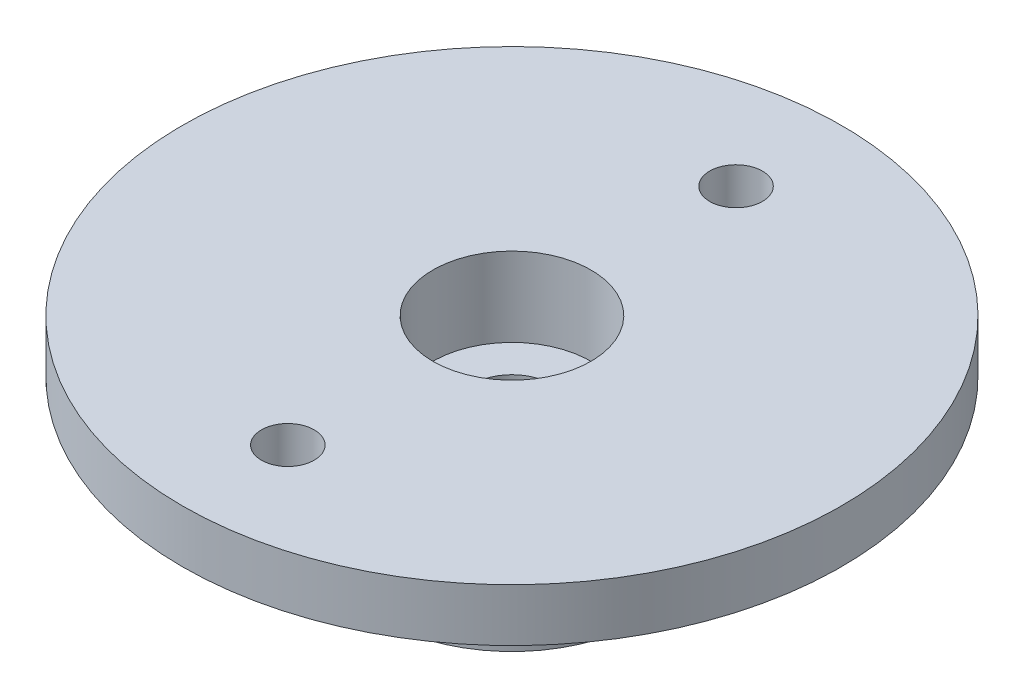
SolidWorks part; units mm, degrees
ref_plane "Front Plane" through (0, 0, 0) normal (0, 0, 1) x (1, 0, 0)
ref_plane "Top Plane" through (0, 0, 0) normal (0, 1, 0) x (1, 0, 0)
ref_plane "Right Plane" through (0, 0, 0) normal (1, 0, 0) x (0, 0, -1)
sketch "Sketch1" plane through (0, 0, 0) normal (0, 1, 0) x (1, 0, 0)
  circle A0 centre (0, 0) radius 12.5
  dimension "D1" = 25
extrude "Boss-Extrude1" add sketch "Sketch1" along normal blind 2
sketch "Sketch2" plane through (0, 0, 0) normal (0, -1, 0) x (1, 0, 0)
  circle A0 centre (0, 0) radius 5
  dimension "D1" = 10
extrude "Boss-Extrude2" add sketch "Sketch2" along normal blind 5.5
sketch "Sketch3" plane through (0, -5.5, 0) normal (0, -1, 0) x (1, 0, 0)
  circle A0 centre (0, 0) radius 2.75
  dimension "D1" = 5.5
extrude "Cut-Extrude1" cut sketch "Sketch3" against normal blind 3
sketch "Sketch4" plane through (0, 2, 0) normal (0, 1, 0) x (1, 0, 0)
  line L0 (0, 8.5) -> (0, -8.5) construction
  circle A0 centre (0, 8.5) radius 1
  circle A1 centre (0, -8.5) radius 1
  dimension "D1" = 2
  dimension "D2" = 15
extrude "Cut-Extrude2" cut sketch "Sketch4" against normal up to next
sketch "Sketch5" plane through (0, 2, 0) normal (0, 1, 0) x (1, 0, 0)
  circle A0 centre (0, 0) radius 3
  dimension "D1" = 6
extrude "Cut-Extrude3" cut sketch "Sketch5" against normal offset from surface (3 mm away) 1.5 up to face at (0, -2.5, -2.75)
sketch "Sketch6" plane through (0, -1, 0) normal (0, 1, 0) x (1, 0, 0)
  circle A0 centre (0, 0) radius 1.5
  dimension "D1" = 3
extrude "Cut-Extrude4" cut sketch "Sketch6" against normal up to next
